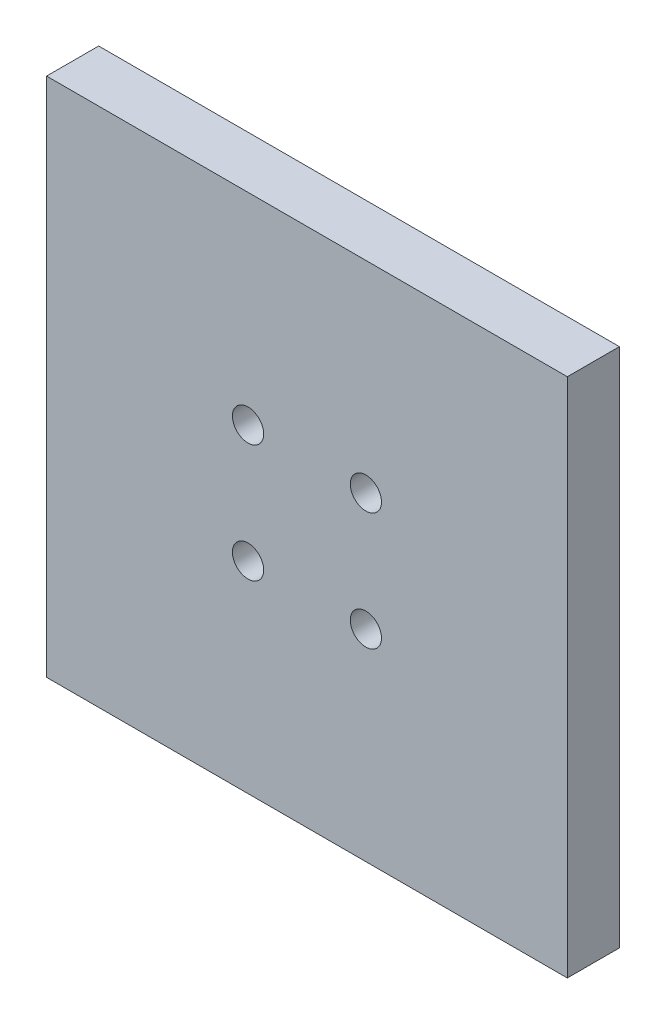
SolidWorks part; units mm, degrees
ref_plane "Front Plane" through (0, 0, 0) normal (0, 0, 1) x (1, 0, 0)
ref_plane "Top Plane" through (0, 0, 0) normal (0, 1, 0) x (1, 0, 0)
ref_plane "Right Plane" through (0, 0, 0) normal (1, 0, 0) x (0, 0, -1)
sketch "Sketch1" plane through (0, 0, 0) normal (0, 0, 1) x (1, 0, 0)
  line L0 (0, 16.2037) -> (0, 0) construction
  line L1 (-25, 25) -> (25, 25)
  line L2 (-25, 25) -> (-25, -25)
  line L3 (-25, -25) -> (25, -25)
  line L4 (25, 25) -> (25, -25)
  line L5 (0, 0) -> (16.821, 0) construction
  point P8 (0, 0)
  point P9 (0, 0)
  point P10 (-27.1605, -25)
  dimension "D1" = 50
  dimension "D2" = 50
extrude "Boss-Extrude1" add sketch "Sketch1" along normal blind 5
sketch "Sketch2" plane through (0, 0, 5) normal (0, 0, 1) x (1, 0, 0)
  line L0 (0, 15.2294) -> (0, 0) construction
  line L1 (0, 0) -> (14.2141, 0) construction
  line L2 (5.6569, 5.6569) -> (-5.6569, -5.6569) construction
  circle A0 centre (0, 0) radius 8 construction
  circle A1 centre (5.6569, 5.6569) radius 1.5
  circle A2 centre (5.6569, -5.6569) radius 1.5
  circle A3 centre (-5.6569, -5.6569) radius 1.5
  circle A4 centre (-5.6569, 5.6569) radius 1.5
  point P17 (0, 0)
  dimension "D1" = 16
  dimension "D3" = 3
  dimension "D2" = 45
  dimension "D4" = 4
extrude "Cut-Extrude1" cut sketch "Sketch2" against normal up to surface (5 mm away) up to face at (0, 0, 0)
